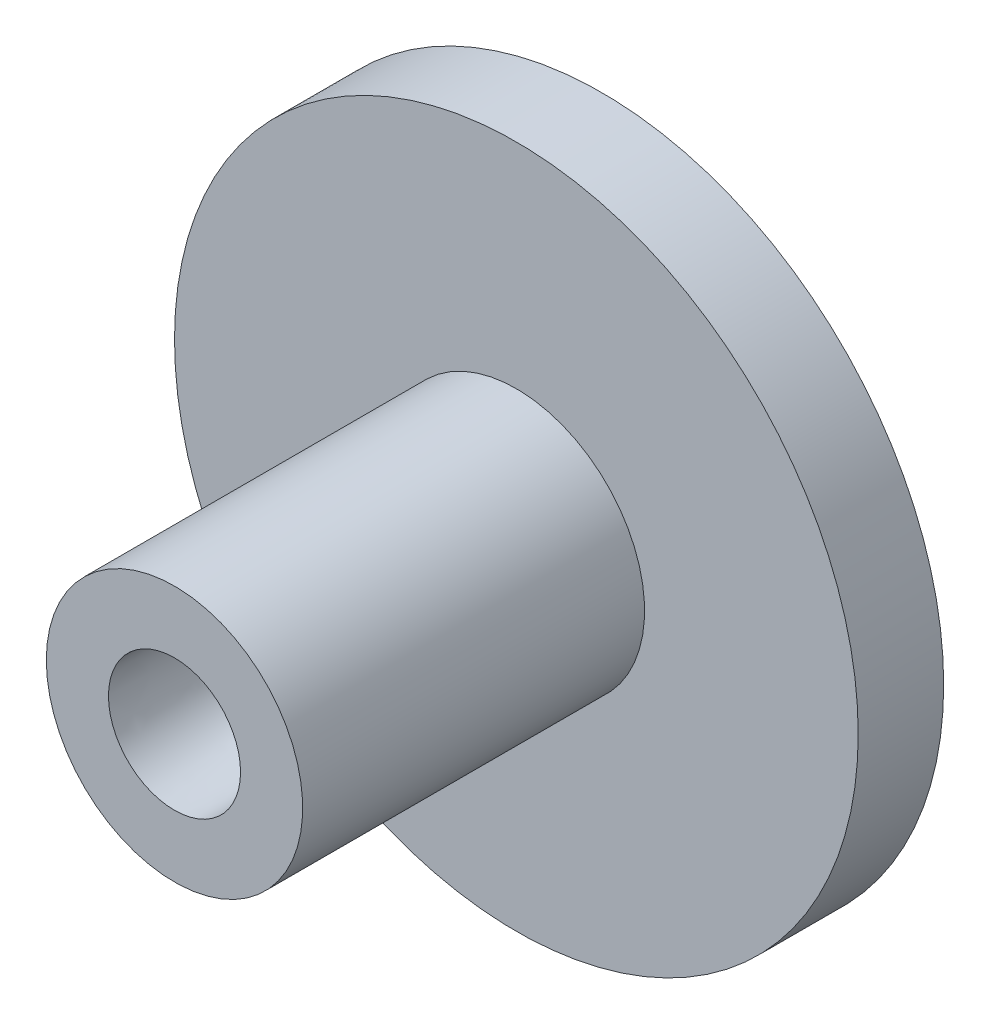
SolidWorks part; units mm, degrees
ref_plane "Front Plane" through (0, 0, 0) normal (0, 0, 1) x (1, 0, 0)
ref_plane "Top Plane" through (0, 0, 0) normal (0, 1, 0) x (1, 0, 0)
ref_plane "Right Plane" through (0, 0, 0) normal (1, 0, 0) x (0, 0, -1)
sketch "Sketch1" plane through (0, 0, 0) normal (0, 0, 1) x (1, 0, 0)
  circle A5 centre (0, 0) radius 20
  point P0 (0, 0)
  dimension "D1" = 40
extrude "Boss-Extrude1" add sketch "Sketch1" along normal blind 5
sketch "Sketch2" plane through (0, 0, 0) normal (0, 1, 0) x (1, 0, 0)
  line L0 (0, 12.7968) -> (0, -30.7792) construction
  line L1 (7.5, -5) -> (7.5, -25)
  line L2 (-20, -5) -> (20, -5) construction
  line L3 (7.5, -25) -> (3.8633, -25)
  line L4 (7.5, -5) -> (0, -5)
  line L5 (0, -5) -> (0, -8.9912)
  spline S0 degree 3 poles (3.8633, -25) (3.6683, -16.6733) (2.8296, -12.9079) (0, -8.9912) knots 0 0 0 0 1 1 1 1
  point P9 (0, -8.9912)
  point P12 (1.8389, -12.1247)
  dimension "D1" = 20
  dimension "D2" = 7.5
revolve "Revolve1" add sketch "Sketch2" angle 360 about L5
